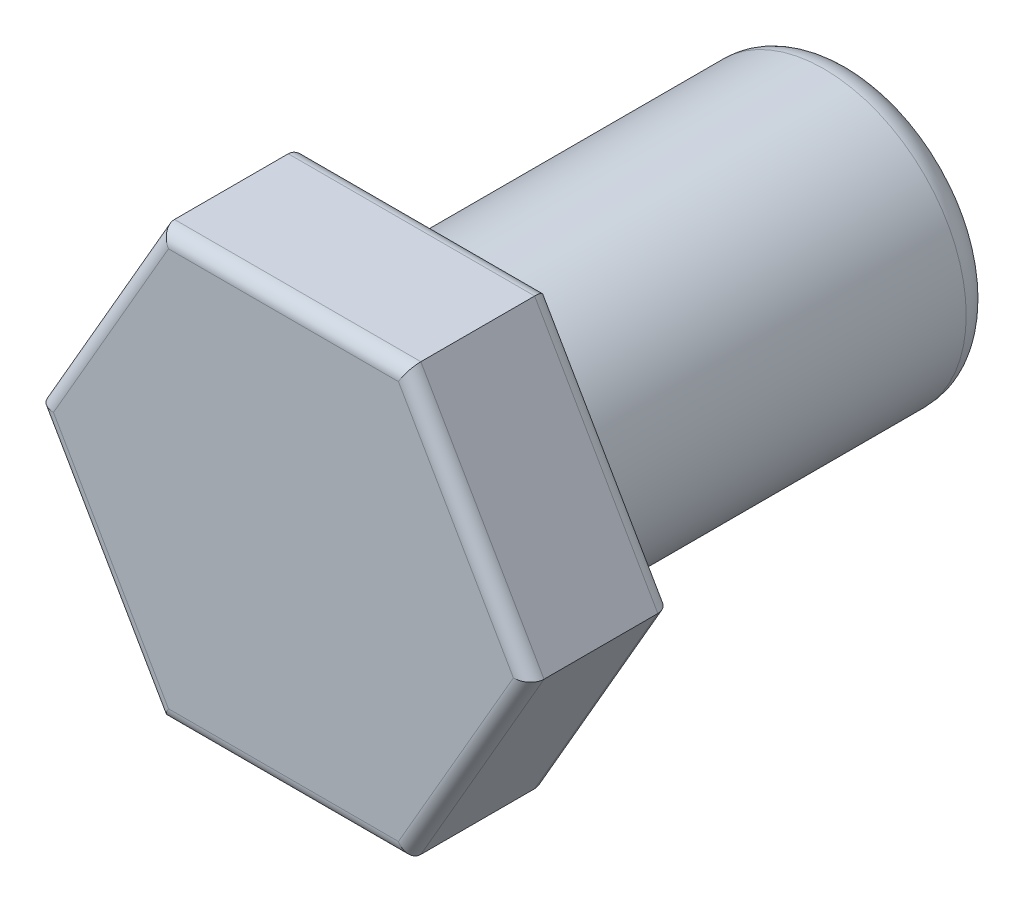
SolidWorks part; units mm, degrees
ref_plane "前视基准面" through (0, 0, 0) normal (0, 0, 1) x (1, 0, 0)
ref_plane "上视基准面" through (0, 0, 0) normal (0, 1, 0) x (1, 0, 0)
ref_plane "右视基准面" through (0, 0, 0) normal (1, 0, 0) x (0, 0, -1)
sketch "草图1" plane through (0, 0, 0) normal (0, 0, 1) x (1, 0, 0)
  circle A0 centre (0, 0) radius 5
  dimension "D1" = 10
extrude "凸台-拉伸1" add sketch "草图1" along normal blind 15
sketch "草图2" plane through (0, 0, 15) normal (0, 0, 1) x (1, 0, 0)
  line L1 (4.3301, -7.5) -> (8.6603, 0)
  line L2 (8.6603, 0) -> (4.3301, 7.5)
  line L3 (4.3301, 7.5) -> (-4.3301, 7.5)
  line L4 (-4.3301, 7.5) -> (-8.6603, 0)
  line L5 (-8.6603, 0) -> (-4.3301, -7.5)
  line L6 (-4.3301, -7.5) -> (4.3301, -7.5)
  circle A0 centre (0, 0) radius 7.5 construction
  dimension "D1" = 15
extrude "凸台-拉伸2" add sketch "草图2" along normal blind 5
fillet "圆角1" radius 0.5 12 edges at (-6.4952, -3.75, 15) (-6.4952, 3.75, 20) (-6.4952, 3.75, 15) (6.4952, -3.75, 15) (6.4952, 3.75, 15) (6.4952, 3.75, 20) (0, 7.5, 20) (0, 7.5, 15) (-6.4952, -3.75, 20) (0, -7.5, 20) (6.4952, -3.75, 20) (0, -7.5, 15)
fillet "圆角2" radius 1 1 edges at (5, 0, 0)
